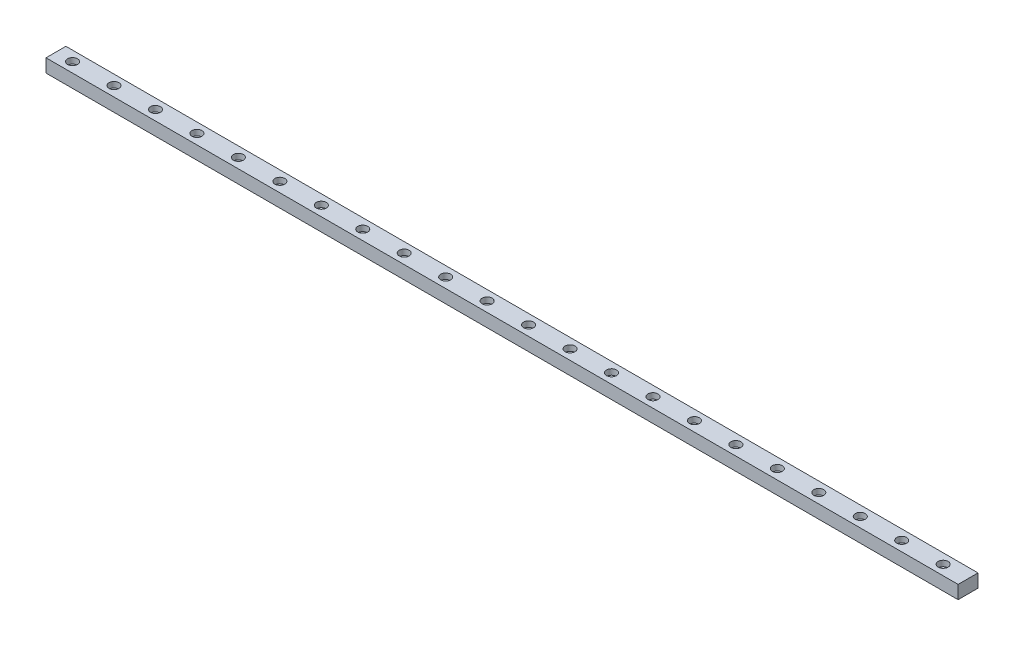
SolidWorks part; units mm, degrees
ref_plane "前基準面" through (0, 0, 0) normal (0, 0, 1) x (1, 0, 0)
ref_plane "上基準面" through (0, 0, 0) normal (0, 1, 0) x (1, 0, 0)
ref_plane "右基準面" through (0, 0, 0) normal (1, 0, 0) x (0, 0, -1)
sketch "草圖1" plane through (0, 0, 0) normal (1, 0, 0) x (0, 0, -1)
  line L0 (0, 0) -> (0, 0.0446) construction
  line L1 (-6, 8) -> (6, 8)
  line L2 (-6, 8) -> (-6, 0)
  line L3 (-6, 0) -> (6, 0)
  line L4 (6, 8) -> (6, 0)
  dimension "D1" = 12
  dimension "D2" = 8
extrude "伸長1" add sketch "草圖1" along normal blind 550
hole_wizard "M3 內六角圓柱頭螺釘的柱孔1" positions "3D草圖1" profile "草圖2" counterbore size "M3" standard "GB" end condition through all
sketch3d "3D草圖1"
  line L0 (0, 8, -6) -> (0, 8, 6) construction
  line L1 (550, 8, 6) -> (0, 8, 6) construction
  point P0 (10, 8, 0)
  dimension "D1" = 10
  dimension "D2" = 6
sketch "草圖2" plane through (10, 8, 0) normal (1, 0, 0) x (0, 0, 1)
  line L0 (0, 0) -> (0, 8)
  line L1 (0, 8) -> (1.6, 8)
  line L3 (1.6, 8) -> (1.6, 3.4)
  line L4 (1.6, 3.4) -> (3, 3.4)
  line L5 (3, 3.4) -> (3, 0)
  line L7 (3, 0) -> (0, 0)
  line L11 (0, -6.35) -> (0, 107.95) construction
  dimension "貫穿孔直徑" = 3.2
  dimension "貫穿孔深度" = 8
  dimension "柱孔直徑" = 6
  dimension "柱孔深度" = 3.4
pattern_linear "直線複製排列1" count 22 spacing 25 along (1, 0, 0) of "M3 內六角圓柱頭螺釘的柱孔1"
